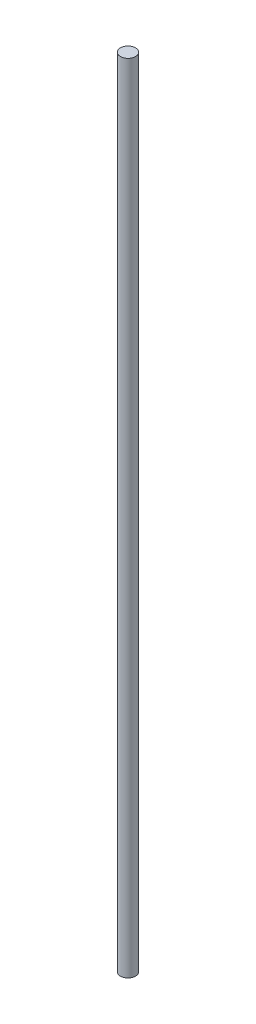
SolidWorks part; units mm, degrees
ref_plane "Front Plane" through (0, 0, 0) normal (0, 0, 1) x (1, 0, 0)
ref_plane "Top Plane" through (0, 0, 0) normal (0, 1, 0) x (1, 0, 0)
ref_plane "Right Plane" through (0, 0, 0) normal (1, 0, 0) x (0, 0, -1)
sketch "Sketch1" plane through (0, 0, 0) normal (0, 1, 0) x (1, 0, 0)
  circle A0 centre (0, 0) radius 4.75
  dimension "D1" = 9.5
extrude "Boss-Extrude1" add sketch "Sketch1" along normal blind 500
